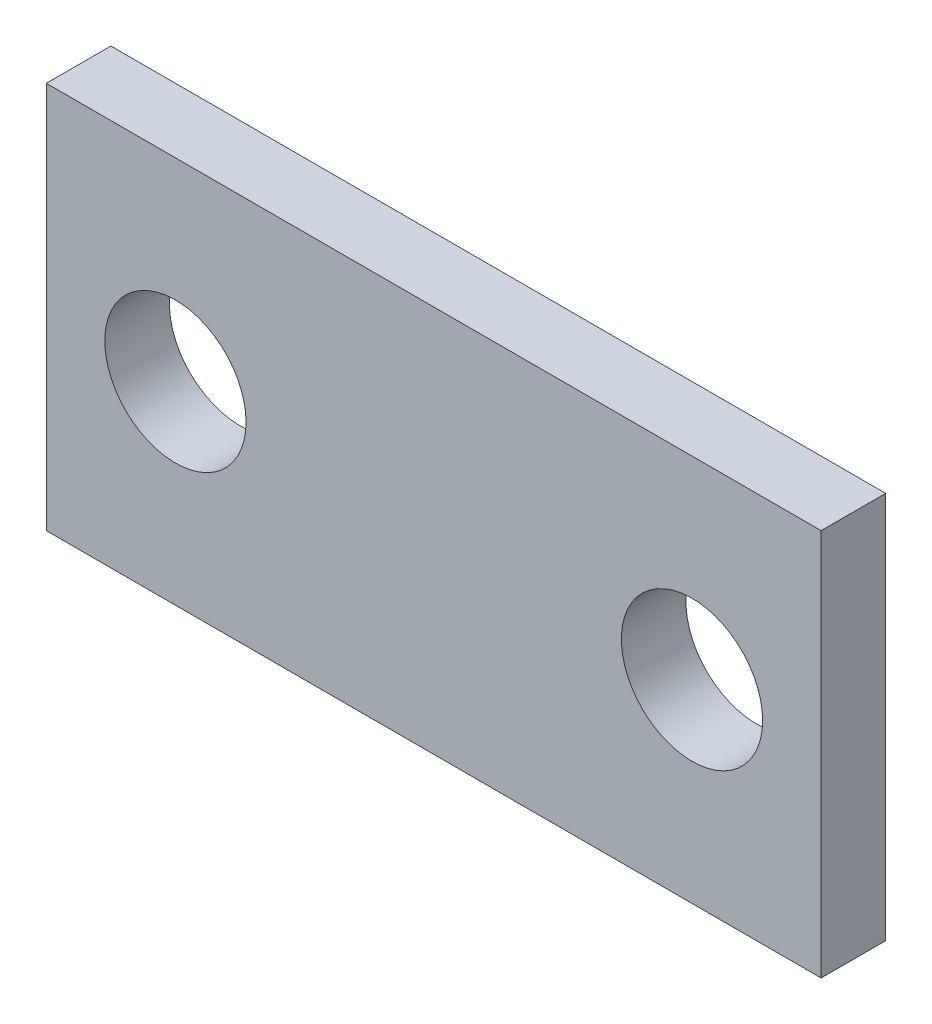
SolidWorks part; units mm, degrees
material "6061-T6 (SS)"
ref_plane "Front" through (0, 0, 0) normal (0, 0, 1) x (1, 0, 0)
ref_plane "Top" through (0, 0, 0) normal (0, 1, 0) x (1, 0, 0)
ref_plane "Right" through (0, 0, 0) normal (1, 0, 0) x (0, 0, -1)
sketch "Sketch1" plane through (0, 0, 0) normal (0, 0, 1) x (1, 0, 0)
  line L1 (-38.1, -19.05) -> (38.1, -19.05)
  line L2 (-38.1, -19.05) -> (-38.1, 19.05)
  line L3 (-38.1, 19.05) -> (38.1, 19.05)
  line L4 (38.1, -19.05) -> (38.1, 19.05)
  line L5 (-38.1, -19.05) -> (38.1, 19.05) construction
  line L6 (-38.1, 19.05) -> (38.1, -19.05) construction
  point P0 (0, 0)
  dimension "D1" = 76.2
  dimension "D2" = 38.1
extrude "Extrude1" add sketch "Sketch1" against normal blind 6.35
hole_wizard "1/2 Clearance Hole1" positions "Sketch3" profile "Sketch2" hole size "1/2" standard "Ansi Inch"
sketch "Sketch3" plane through (0, 0, 0) normal (0, 0, 1) x (1, 0, 0)
  line L4 (-38.1, 0) -> (38.1, 0) construction
  line L5 (-38.1, 19.05) -> (-38.1, -19.05) construction
  line L6 (38.1, -19.05) -> (38.1, 19.05) construction
  point P0 (-25.4, 0)
  point P1 (25.4, 0)
  dimension "D1" = 25.4
  dimension "D2" = 25.4
sketch "Sketch2" plane through (-25.4, 0, 0) normal (1, 0, 0) x (0, -1, 0)
  line L0 (0, 0) -> (0, 10.5234)
  line L1 (0, 10.5234) -> (6.9456, 6.35)
  line L2 (6.9456, 6.35) -> (6.9456, 0)
  line L5 (6.9456, 0) -> (0, 0)
  line L10 (0, 10.5234) -> (-6.9456, 6.35) construction
  line L11 (0, -6.35) -> (0, 107.95) construction
  dimension "Hole Dia." = 13.8913
  dimension "Hole Depth" = 6.35
  dimension "Drill Angle" = 118
